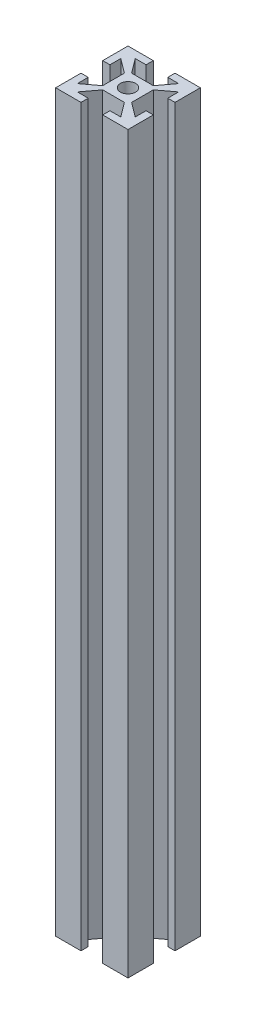
SolidWorks part; units mm, degrees
material "5052-H34"
ref_plane "Front Plane" through (0, 0, 0) normal (0, 0, 1) x (1, 0, 0)
ref_plane "Top Plane" through (0, 0, 0) normal (0, 1, 0) x (1, 0, 0)
ref_plane "Right Plane" through (0, 0, 0) normal (1, 0, 0) x (0, 0, -1)
sketch "Sketch1" plane through (0, 0, 0) normal (0, 1, 0) x (1, 0, 0)
  line L1 (-10, -10) -> (10, -10)
  line L2 (-10, -10) -> (-10, 10)
  line L3 (-10, 10) -> (10, 10)
  line L4 (10, -10) -> (10, 10)
  line L5 (-10, -10) -> (10, 10) construction
  line L6 (-10, 10) -> (10, -10) construction
  point P0 (0, 0)
  dimension "D1" = 20
  dimension "D2" = 20
extrude "Boss-Extrude1" add sketch "Sketch1" along normal mid plane 203.2
sketch "Sketch2" plane through (0, 101.6, 0) normal (0, 1, 0) x (1, 0, 0)
  line L0 (-16.678, 0) -> (16.678, 0) construction
  line L1 (0, -16.9461) -> (0, 16.9461) construction
  line L2 (-10, -3) -> (-10, 3)
  line L3 (-8, -6) -> (-8, -3)
  line L4 (-10, 10) -> (-10, -10) construction
  line L5 (-10, 3) -> (-8, 3)
  line L6 (-10, -3) -> (-8, -3)
  line L7 (-4, -3) -> (-4, 3)
  line L8 (-4, -4) -> (4, -4) construction
  line L9 (-4, -4) -> (-4, 4) construction
  line L10 (-4, 4) -> (4, 4) construction
  line L11 (4, -4) -> (4, 4) construction
  line L12 (-4, -4) -> (4, 4) construction
  line L13 (-4, 4) -> (4, -4) construction
  line L14 (-4, 3) -> (-8, 6)
  line L15 (-4, -3) -> (-8, -6)
  line L16 (-8, 3) -> (-8, 6)
  line L17 (3, 4) -> (6, 8)
  line L18 (3, 8) -> (6, 8)
  line L19 (3, 10) -> (3, 8)
  line L20 (-3, 10) -> (3, 10)
  line L21 (-3, 10) -> (-3, 8)
  line L22 (-6, 8) -> (-3, 8)
  line L23 (-3, 4) -> (-6, 8)
  line L24 (-3, 4) -> (3, 4)
  line L25 (4, -3) -> (8, -6)
  line L26 (8, -3) -> (8, -6)
  line L27 (10, -3) -> (8, -3)
  line L28 (10, 3) -> (10, -3)
  line L29 (10, 3) -> (8, 3)
  line L30 (8, 6) -> (8, 3)
  line L31 (4, 3) -> (8, 6)
  line L32 (4, 3) -> (4, -3)
  line L33 (-3, -4) -> (-6, -8)
  line L34 (-3, -8) -> (-6, -8)
  line L35 (-3, -10) -> (-3, -8)
  line L36 (3, -10) -> (-3, -10)
  line L37 (3, -10) -> (3, -8)
  line L38 (6, -8) -> (3, -8)
  line L39 (3, -4) -> (6, -8)
  line L40 (3, -4) -> (-3, -4)
  point P4 (0, 0)
  point P8 (0, 0)
  point P11 (-10, 0)
  point P14 (-8, 0)
  point P16 (0, 0)
  point P26 (-4, 0)
  point P53 (0, 0)
  dimension "D1" = 6
  dimension "D2" = 12
  dimension "D3" = 2
  dimension "D4" = 8
  dimension "D5" = 8
  dimension "D6" = 6
  dimension "D7" = 4
extrude "Cut-Extrude1" cut sketch "Sketch2" against normal blind 203.2
sketch "Sketch3" plane through (0, 101.6, 0) normal (0, 1, 0) x (1, 0, 0)
  circle A0 centre (0, 0) radius 2.1
  dimension "D1" = 4.2
extrude "Cut-Extrude2" cut sketch "Sketch3" against normal blind 13
sketch "Sketch4" plane through (0, -101.6, 0) normal (0, -1, 0) x (1, 0, 0)
  circle A0 centre (0, 0) radius 2.1
  dimension "D1" = 4.2
extrude "Cut-Extrude3" cut sketch "Sketch4" against normal blind 13
